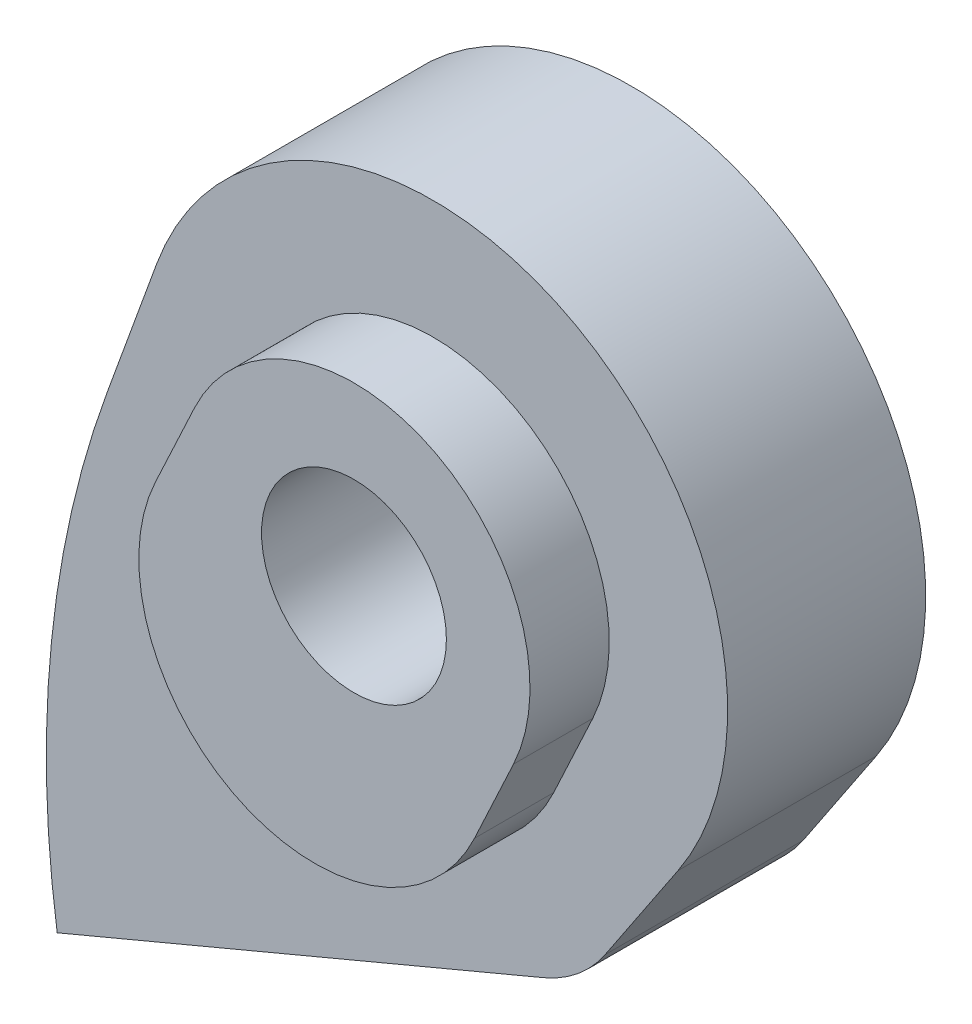
SolidWorks part; units mm, degrees
ref_plane "Front Plane" through (0, 0, 0) normal (0, 0, 1) x (1, 0, 0)
ref_plane "Top Plane" through (0, 0, 0) normal (0, 1, 0) x (1, 0, 0)
ref_plane "Right Plane" through (0, 0, 0) normal (1, 0, 0) x (0, 0, -1)
sketch "Sketch6" plane through (0, 0, 0) normal (0, 0, 1) x (1, 0, 0)
  line L0 (0, 0) -> (40.1809, 0) construction
  line L1 (0, 0) -> (35.507, 92.499) construction
  line L2 (19.3519, 50.4133) -> (0.4719, 63.0164) construction
  line L3 (19.3519, 50.4133) -> (-36.1025, 71.7003) construction
  dimension "D1" = 69
  dimension "D2" = 54
  dimension "D3" = 22.7
  dimension "D4" = 5
sketch "Sketch3" plane through (0, 0, 0) normal (0, 0, 1) x (1, 0, 0)
  line L0 (24.1743, 72.523) -> (120.8717, 72.523) construction
  line L6 (11.8164, 60.2529) -> (11.7284, 60.3116)
  line L7 (7.3748, 53.5992) -> (5.9136, 54.5745)
  line L8 (19.3519, 50.4133) -> (0.4719, 63.0164) construction
  line L9 (-6.1719, 82.4206) -> (-7.2903, 79.3479)
  line L10 (19.3519, 50.4133) -> (13.2479, 41.2693) construction
  line L11 (19.3519, 50.4133) -> (31.6629, 68.8558) construction
  line L12 (4.0204, 73.9337) -> (5.6789, 76.4182)
  line L14 (0.1147, 80.1325) -> (27.1455, 62.0885) construction
  line L15 (0.1147, 80.1325) -> (-7.2903, 79.3479) construction
  line L16 (0.1147, 80.1325) -> (0.1147, 91.1913) construction
  line L17 (0.1147, 80.1325) -> (-6.1719, 82.4206) construction
  arc A0 (13.4996, 47.0498) -> (20.2139, 57.1081) centre (19.3519, 50.4133) ccw
  arc A1 (20.2139, 57.1081) -> (11.8164, 60.2529) centre (22.7223, 76.5904) cw
  arc A2 (13.4996, 47.0498) -> (7.3748, 53.5992) centre (-3.5311, 37.2616) ccw
  arc A3 (11.7284, 60.3116) -> (6.8662, 65.9311) centre (19.4923, 71.9424) cw
  arc A4 (-6.1719, 82.4206) -> (5.6789, 76.4182) centre (0.1147, 80.1325) cw
  arc A5 (6.8662, 65.9311) -> (4.9012, 68.3908) centre (0.6246, 62.9595) ccw
  arc A6 (4.9012, 68.3908) -> (4.0204, 73.9337) centre (7.4585, 71.6386) cw
  arc A7 (5.9136, 54.5745) -> (0.4148, 56.2666) centre (0.3298, 46.2096) ccw
  arc A10 (0.4148, 56.2666) -> (-5.2798, 59.4837) centre (0.4719, 63.0164) cw
  circle A12 centre (19.3519, 50.4133) radius 2.75
  circle A13 centre (0.4719, 63.0164) radius 2.75
  circle A17 centre (0.1147, 80.1325) radius 2.1
  arc A18 (-7.2903, 79.3479) -> (-5.2798, 59.4837) centre (14.2795, 71.4971) ccw
  dimension "D1" = 5.5
  dimension "D2" = 5.5
  dimension "D3" = 4
  dimension "D5" = 4
  dimension "D6" = 4
  dimension "D4" = 4.2
  dimension "D17" = 70
  dimension "D18" = 3.27
  dimension "D14" = 6.69
  dimension "D7" = 3
  dimension "D8" = 4
  dimension "D9" = 3
  dimension "D10" = 4
  dimension "D11" = 19
  dimension "D12" = 19
  dimension "D13" = 22
  dimension "D15" = 32.5
  dimension "D16" = 14
extrude "Boss-Extrude2" add sketch "Sketch3" along normal blind 11
sketch "Sketch13" plane through (0, 0, 0) normal (0, 0, -1) x (-1, 0, 0)
  line L0 (-5.6789, 76.4182) -> (-4.0204, 73.9337)
  line L1 (-2.6258, 72.7829) -> (8.4277, 68.1397)
  line L2 (6.1719, 82.4206) -> (7.2903, 79.3479)
  arc A0 (-5.6789, 76.4182) -> (6.1719, 82.4206) centre (-0.1147, 80.1325) cw
  arc A1 (6.1719, 82.4206) -> (-5.6789, 76.4182) centre (-0.1147, 80.1325) ccw construction
  arc A2 (-4.0204, 73.9337) -> (-2.6258, 72.7829) centre (-1.4106, 75.6758) ccw
  arc A3 (5.2798, 59.4837) -> (7.2903, 79.3479) centre (-14.2795, 71.4971) ccw construction
  arc A4 (8.4277, 68.1397) -> (7.2903, 79.3479) centre (-14.2795, 71.4971) ccw
extrude "Boss-Extrude4" add sketch "Sketch13" along normal blind 4.5
sketch "Sketch12" plane through (0, 0, -4.5) normal (0, 0, -1) x (-1, 0, 0)
  line L0 (8.0136, 76.9658) -> (4.9242, 69.6114)
  line L4 (4.9242, 69.6114) -> (8.4277, 68.1397)
  line L5 (-2.6258, 72.7829) -> (8.4277, 68.1397) construction
  line L8 (-2.6258, 72.7829) -> (8.4277, 68.1397) construction
  arc A0 (8.0136, 76.9658) -> (8.4277, 68.1397) centre (-14.2795, 71.4971) cw
  arc A1 (5.2798, 59.4837) -> (8.4277, 68.1397) centre (-14.2795, 71.4971) ccw construction
  dimension "D1" = 3.8
  dimension "D2" = 90
extrude "Boss-Extrude3" add sketch "Sketch12" along normal blind 3
sketch "Sketch14" plane through (0, 0, 0) normal (0, 1, 0) x (1, 0, 0)
  line L0 (19.3519, 0) -> (-36.1025, 0) construction
  line L1 (-15.2308, 0) -> (32.0549, 0)
  line L2 (-15.2308, 0) -> (-15.2308, -12.5955)
  line L3 (-15.2308, -12.5955) -> (32.0549, -12.5955)
  line L4 (32.0549, 0) -> (32.0549, -12.5955)
extrude "Cut-Extrude1" cut sketch "Sketch14" along normal through all
sketch "Sketch16" plane through (0, 0, 0) normal (0, 0, 1) x (1, 0, 0)
  line L0 (0.1147, 80.1325) -> (-0.7728, 78.2293) construction
  line L1 (3.7399, 78.4421) -> (2.8524, 76.5388)
  line L2 (-3.5105, 81.823) -> (-4.398, 79.9198)
  line L3 (0.1147, 80.1325) -> (0.1147, 75.6752) construction
  arc A0 (3.7399, 78.4421) -> (-3.5105, 81.823) centre (0.1147, 80.1325) ccw
  arc A1 (-4.398, 79.9198) -> (2.8524, 76.5388) centre (-0.7728, 78.2293) ccw
  point P3 (-0.3291, 79.1809)
  dimension "D1" = 4
  dimension "D2" = 25
  dimension "D3" = 2.1
extrude "Boss-Extrude5" add sketch "Sketch16" along normal blind 1.8
sketch "Sketch15" plane through (0, 0, 1.8) normal (0, 0, 1) x (1, 0, 0)
  circle A0 centre (0.1147, 80.1325) radius 2.1
  dimension "D1" = 4.2
extrude "Cut-Extrude2" cut sketch "Sketch15" against normal through all
